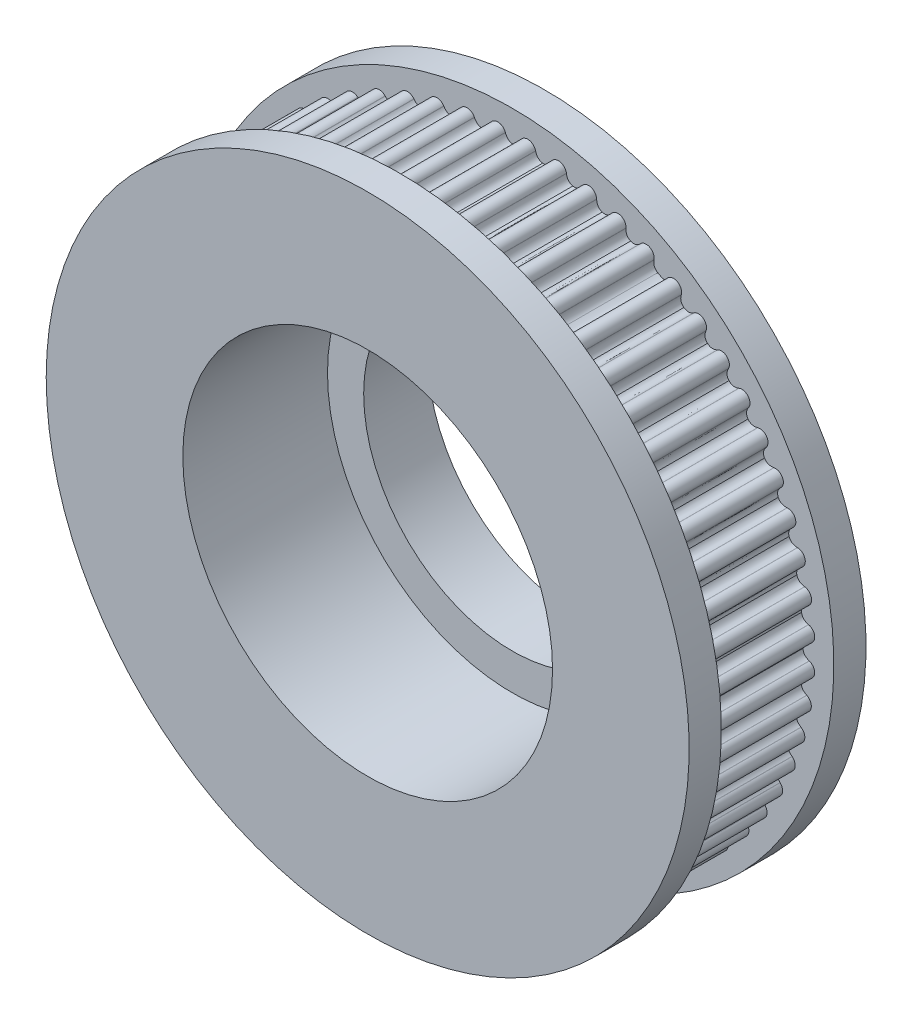
SolidWorks part; units mm, degrees
other "Camera1"
other "Camera2"
other "Camera3"
ref_plane "Front" through (0, 0, 0) normal (0, 0, 1) x (1, 0, 0)
ref_plane "Top" through (0, 0, 0) normal (0, 1, 0) x (1, 0, 0)
ref_plane "Right" through (0, 0, 0) normal (1, 0, 0) x (0, 0, -1)
sketch "Sketch1" plane through (0, 0, 0) normal (1, 0, 0) x (0, 0, -1)
  line L0 (0, 0) -> (-24.4032, 0) construction
  line L2 (0, 11.25) -> (-2, 11.25)
  line L3 (-2, 11.5) -> (-2, 18.85)
  line L4 (-4, 18.85) -> (-11, 18.85)
  line L5 (-13, 18.85) -> (-13, 11.5)
  line L6 (-13, 11.5) -> (-4, 11.5)
  line L7 (-2, 18.85) -> (-2, 20)
  line L9 (-4, 20) -> (-4, 18.85)
  line L10 (-13, 13.3586) -> (-2, 13.3586) construction
  line L11 (-7.5, 18.85) -> (-7.5, 22.0506) construction
  line L12 (-11, 20) -> (-11, 18.85)
  line L14 (-13, 18.85) -> (-13, 20)
  line L15 (-13, 18.85) -> (-11, 18.85) construction
  line L16 (-4, 18.85) -> (-2, 18.85) construction
  line L17 (-13, 20) -> (-11, 20)
  line L18 (-4, 20) -> (-2, 20)
  line L22 (-4, 11.5) -> (-4, 9.25)
  line L23 (-4, 9.25) -> (0, 9.25)
  line L24 (0, 9.25) -> (0, 11.25)
  line L25 (-2, 11.5) -> (-2, 11.25)
  point P24 (-7.5, 13.3586)
  dimension "D2" = 11
  dimension "D3" = 7
  dimension "D4" = 37.7
  dimension "D5" = 40
  dimension "D6" = 2
  dimension "D7" = 22.5
  dimension "D8" = 23
  dimension "D10" = 2
revolve "Revolve1" add sketch "Sketch1" angle 360 about L0
ref_plane "Plane2" through (0, 0, 4) normal (0, 0, 1) x (1, 0, 0)
ref_plane "Plane3" through (0, 0, 11) normal (0, 0, -1) x (-1, 0, 0)
sketch "Sketch3" plane through (0, 0, 4) normal (0, 0, 1) x (1, 0, 0)
  line L0 (0.4895, 18.4804) -> (0.4858, 18.4697)
  line L1 (-0.4323, 18.471) -> (-0.436, 18.4817)
  line L2 (-1.3914, 18.4344) -> (-1.394, 18.4234)
  line L3 (-2.3607, 18.3247) -> (-2.3654, 18.3349)
  line L4 (-3.3107, 18.188) -> (-3.3122, 18.1768)
  line L5 (-4.2632, 17.9775) -> (-4.269, 17.9872)
  line L6 (-5.1937, 17.7423) -> (-5.194, 17.731)
  line L7 (-6.119, 17.4334) -> (-6.1258, 17.4424)
  line L8 (-7.0199, 17.1022) -> (-7.019, 17.0909)
  line L9 (-7.9078, 16.6983) -> (-7.9155, 16.7066)
  line L10 (-8.7691, 16.2747) -> (-8.767, 16.2636)
  line L11 (-9.6099, 15.7803) -> (-9.6184, 15.7877)
  line L12 (-10.4222, 15.269) -> (-10.419, 15.2581)
  line L13 (-11.2067, 14.6893) -> (-11.216, 14.6958)
  line L14 (-11.9612, 14.0959) -> (-11.9568, 14.0855)
  line L15 (-12.6808, 13.4374) -> (-12.6907, 13.4429)
  line L16 (-13.3691, 12.7684) -> (-13.3637, 12.7585)
  line L17 (-14.0159, 12.0383) -> (-14.0263, 12.0427)
  line L18 (-14.6305, 11.301) -> (-14.6241, 11.2917)
  line L19 (-15.1975, 10.5073) -> (-15.2083, 10.5106)
  line L20 (-15.7316, 9.7098) -> (-15.7243, 9.7012)
  line L21 (-16.2125, 8.8612) -> (-16.2236, 8.8633)
  line L22 (-16.6604, 8.0122) -> (-16.6522, 8.0044)
  line L23 (-17.05, 7.118) -> (-17.0612, 7.1189)
  line L24 (-17.4066, 6.2268) -> (-17.3977, 6.22)
  line L25 (-17.7006, 5.2968) -> (-17.7119, 5.2965)
  line L26 (-17.9621, 4.3732) -> (-17.9525, 4.3673)
  line L27 (-18.1573, 3.4175) -> (-18.1685, 3.4161)
  line L28 (-18.3209, 2.4717) -> (-18.3107, 2.4669)
  line L29 (-18.415, 1.5008) -> (-18.426, 1.4983)
  line L30 (-18.4789, 0.5431) -> (-18.4682, 0.5394)
  line L31 (-18.471, -0.4323) -> (-18.4817, -0.436)
  line L32 (-18.4344, -1.3914) -> (-18.4234, -1.394)
  line L33 (-18.3247, -2.3607) -> (-18.3349, -2.3654)
  line L34 (-18.188, -3.3107) -> (-18.1768, -3.3122)
  line L35 (-17.9775, -4.2632) -> (-17.9872, -4.269)
  line L36 (-17.7423, -5.1937) -> (-17.731, -5.194)
  line L37 (-17.4334, -6.119) -> (-17.4424, -6.1258)
  line L38 (-17.1022, -7.0199) -> (-17.0909, -7.019)
  line L39 (-16.6983, -7.9078) -> (-16.7066, -7.9155)
  line L40 (-16.2747, -8.7691) -> (-16.2636, -8.767)
  line L41 (-15.7803, -9.6099) -> (-15.7877, -9.6184)
  line L42 (-15.269, -10.4222) -> (-15.2581, -10.419)
  line L43 (-14.6893, -11.2067) -> (-14.6958, -11.216)
  line L44 (-14.0959, -11.9612) -> (-14.0855, -11.9568)
  line L45 (-13.4374, -12.6808) -> (-13.4429, -12.6907)
  line L46 (-12.7684, -13.3691) -> (-12.7585, -13.3637)
  line L47 (-12.0383, -14.0159) -> (-12.0427, -14.0263)
  line L48 (-11.301, -14.6305) -> (-11.2917, -14.6241)
  line L49 (-10.5073, -15.1975) -> (-10.5106, -15.2083)
  line L50 (-9.7098, -15.7316) -> (-9.7012, -15.7243)
  line L51 (-8.8612, -16.2125) -> (-8.8633, -16.2236)
  line L52 (-8.0122, -16.6604) -> (-8.0044, -16.6522)
  line L53 (-7.118, -17.05) -> (-7.1189, -17.0612)
  line L54 (-6.2268, -17.4066) -> (-6.22, -17.3977)
  line L55 (-5.2968, -17.7006) -> (-5.2965, -17.7119)
  line L56 (-4.3732, -17.9621) -> (-4.3673, -17.9525)
  line L57 (-3.4175, -18.1573) -> (-3.4161, -18.1685)
  line L58 (-2.4717, -18.3209) -> (-2.4669, -18.3107)
  line L59 (-1.5008, -18.415) -> (-1.4983, -18.426)
  line L60 (-0.5431, -18.4789) -> (-0.5394, -18.4682)
  line L61 (0.4323, -18.471) -> (0.436, -18.4817)
  line L62 (1.3914, -18.4344) -> (1.394, -18.4234)
  line L63 (2.3607, -18.3247) -> (2.3654, -18.3349)
  line L64 (3.3107, -18.188) -> (3.3122, -18.1768)
  line L65 (4.2632, -17.9775) -> (4.269, -17.9872)
  line L66 (5.1937, -17.7423) -> (5.194, -17.731)
  line L67 (6.119, -17.4334) -> (6.1258, -17.4424)
  line L68 (7.0199, -17.1022) -> (7.019, -17.0909)
  line L69 (7.9078, -16.6983) -> (7.9155, -16.7066)
  line L70 (8.7691, -16.2747) -> (8.767, -16.2636)
  line L71 (9.6099, -15.7803) -> (9.6184, -15.7877)
  line L72 (10.4222, -15.269) -> (10.419, -15.2581)
  line L73 (11.2067, -14.6893) -> (11.216, -14.6958)
  line L74 (11.9612, -14.0959) -> (11.9568, -14.0855)
  line L75 (12.6808, -13.4374) -> (12.6907, -13.4429)
  line L76 (13.3691, -12.7684) -> (13.3637, -12.7585)
  line L77 (14.0159, -12.0383) -> (14.0263, -12.0427)
  line L78 (14.6305, -11.301) -> (14.6241, -11.2917)
  line L79 (15.1975, -10.5073) -> (15.2083, -10.5106)
  line L80 (15.7316, -9.7098) -> (15.7243, -9.7012)
  line L81 (16.2125, -8.8612) -> (16.2236, -8.8633)
  line L82 (16.6604, -8.0122) -> (16.6522, -8.0044)
  line L83 (17.05, -7.118) -> (17.0612, -7.1189)
  line L84 (17.4066, -6.2268) -> (17.3977, -6.22)
  line L85 (17.7006, -5.2968) -> (17.7119, -5.2965)
  line L86 (17.9621, -4.3732) -> (17.9525, -4.3673)
  line L87 (18.1573, -3.4175) -> (18.1685, -3.4161)
  line L88 (18.3209, -2.4717) -> (18.3107, -2.4669)
  line L89 (18.415, -1.5008) -> (18.426, -1.4983)
  line L90 (18.4789, -0.5431) -> (18.4682, -0.5394)
  line L91 (18.471, 0.4323) -> (18.4817, 0.436)
  line L92 (18.4344, 1.3914) -> (18.4234, 1.394)
  line L93 (18.3247, 2.3607) -> (18.3349, 2.3654)
  line L94 (18.188, 3.3107) -> (18.1768, 3.3122)
  line L95 (17.9775, 4.2632) -> (17.9872, 4.269)
  line L96 (17.7423, 5.1937) -> (17.731, 5.194)
  line L97 (17.4334, 6.119) -> (17.4424, 6.1258)
  line L98 (17.1022, 7.0199) -> (17.0909, 7.019)
  line L99 (16.6983, 7.9078) -> (16.7066, 7.9155)
  line L100 (16.2747, 8.7691) -> (16.2636, 8.767)
  line L101 (15.7803, 9.6099) -> (15.7877, 9.6184)
  line L102 (15.269, 10.4222) -> (15.2581, 10.419)
  line L103 (14.6893, 11.2067) -> (14.6958, 11.216)
  line L104 (14.0959, 11.9612) -> (14.0855, 11.9568)
  line L105 (13.4374, 12.6808) -> (13.4429, 12.6907)
  line L106 (12.7684, 13.3691) -> (12.7585, 13.3637)
  line L107 (12.0383, 14.0159) -> (12.0427, 14.0263)
  line L108 (11.301, 14.6305) -> (11.2917, 14.6241)
  line L109 (10.5073, 15.1975) -> (10.5106, 15.2083)
  line L110 (9.7098, 15.7316) -> (9.7012, 15.7243)
  line L111 (8.8141, 16.2382) -> (8.8162, 16.2492)
  line L112 (7.9639, 16.6835) -> (7.9561, 16.6753)
  line L113 (7.0685, 17.0705) -> (7.0694, 17.0818)
  line L114 (6.1763, 17.4246) -> (6.1695, 17.4156)
  line L115 (5.2454, 17.7159) -> (5.2452, 17.7272)
  line L116 (4.3211, 17.9748) -> (4.3153, 17.9651)
  line L117 (3.3649, 18.1671) -> (3.3634, 18.1783)
  line L118 (2.4186, 18.328) -> (2.4138, 18.3178)
  line L119 (1.4475, 18.4193) -> (1.4449, 18.4303)
  arc A0 (-0.436, 18.4817) -> (-1.3914, 18.4344) centre (-0.9065, 18.3126) ccw
  arc A1 (-2.3654, 18.3349) -> (-3.3107, 18.188) centre (-2.8157, 18.1175) ccw
  arc A2 (-4.269, 17.9872) -> (-5.1937, 17.7423) centre (-4.6941, 17.7239) ccw
  arc A3 (-6.1258, 17.4424) -> (-7.0199, 17.1022) centre (-6.521, 17.1362) ccw
  arc A4 (-7.9155, 16.7066) -> (-8.7691, 16.2747) centre (-8.2765, 16.3607) ccw
  arc A5 (-9.6184, 15.7877) -> (-10.4222, 15.269) centre (-9.9413, 15.4059) ccw
  arc A6 (-11.216, 14.6958) -> (-11.9612, 14.0959) centre (-11.4972, 14.2824) ccw
  arc A7 (-12.6907, 13.4429) -> (-13.3691, 12.7684) centre (-12.9272, 13.0023) ccw
  arc A8 (-14.0263, 12.0427) -> (-14.6305, 11.301) centre (-14.2155, 11.5798) ccw
  arc A9 (-15.2083, 10.5106) -> (-15.7316, 9.7098) centre (-15.348, 10.0305) ccw
  arc A10 (-16.2236, 8.8633) -> (-16.6604, 8.0122) centre (-16.3124, 8.3712) ccw
  arc A11 (-17.0612, 7.1189) -> (-17.4066, 6.2268) centre (-17.0981, 6.6203) ccw
  arc A12 (-17.7119, 5.2965) -> (-17.9621, 4.3732) centre (-17.6964, 4.7968) ccw
  arc A13 (-18.1685, 3.4161) -> (-18.3209, 2.4717) centre (-18.1009, 2.9207) ccw
  arc A14 (-18.426, 1.4983) -> (-18.4789, 0.5431) centre (-18.307, 1.0127) ccw
  arc A15 (-18.4817, -0.436) -> (-18.4344, -1.3914) centre (-18.3126, -0.9065) ccw
  arc A16 (-18.3349, -2.3654) -> (-18.188, -3.3107) centre (-18.1175, -2.8157) ccw
  arc A17 (-17.9872, -4.269) -> (-17.7423, -5.1937) centre (-17.7239, -4.6941) ccw
  arc A18 (-17.4424, -6.1258) -> (-17.1022, -7.0199) centre (-17.1362, -6.521) ccw
  arc A19 (-16.7066, -7.9155) -> (-16.2747, -8.7691) centre (-16.3607, -8.2765) ccw
  arc A20 (-15.7877, -9.6184) -> (-15.269, -10.4222) centre (-15.4059, -9.9413) ccw
  arc A21 (-14.6958, -11.216) -> (-14.0959, -11.9612) centre (-14.2824, -11.4972) ccw
  arc A22 (-13.4429, -12.6907) -> (-12.7684, -13.3691) centre (-13.0023, -12.9272) ccw
  arc A23 (-12.0427, -14.0263) -> (-11.301, -14.6305) centre (-11.5798, -14.2155) ccw
  arc A24 (-10.5106, -15.2083) -> (-9.7098, -15.7316) centre (-10.0305, -15.348) ccw
  arc A25 (-8.8633, -16.2236) -> (-8.0122, -16.6604) centre (-8.3712, -16.3124) ccw
  arc A26 (-7.1189, -17.0612) -> (-6.2268, -17.4066) centre (-6.6203, -17.0981) ccw
  arc A27 (-5.2965, -17.7119) -> (-4.3732, -17.9621) centre (-4.7968, -17.6964) ccw
  arc A28 (-3.4161, -18.1685) -> (-2.4717, -18.3209) centre (-2.9207, -18.1009) ccw
  arc A29 (-1.4983, -18.426) -> (-0.5431, -18.4789) centre (-1.0127, -18.307) ccw
  arc A30 (0.436, -18.4817) -> (1.3914, -18.4344) centre (0.9065, -18.3126) ccw
  arc A31 (2.3654, -18.3349) -> (3.3107, -18.188) centre (2.8157, -18.1175) ccw
  arc A32 (4.269, -17.9872) -> (5.1937, -17.7423) centre (4.6941, -17.7239) ccw
  arc A33 (6.1258, -17.4424) -> (7.0199, -17.1022) centre (6.521, -17.1362) ccw
  arc A34 (7.9155, -16.7066) -> (8.7691, -16.2747) centre (8.2765, -16.3607) ccw
  arc A35 (9.6184, -15.7877) -> (10.4222, -15.269) centre (9.9413, -15.4059) ccw
  arc A36 (11.216, -14.6958) -> (11.9612, -14.0959) centre (11.4972, -14.2824) ccw
  arc A37 (12.6907, -13.4429) -> (13.3691, -12.7684) centre (12.9272, -13.0023) ccw
  arc A38 (14.0263, -12.0427) -> (14.6305, -11.301) centre (14.2155, -11.5798) ccw
  arc A39 (15.2083, -10.5106) -> (15.7316, -9.7098) centre (15.348, -10.0305) ccw
  arc A40 (16.2236, -8.8633) -> (16.6604, -8.0122) centre (16.3124, -8.3712) ccw
  arc A41 (17.0612, -7.1189) -> (17.4066, -6.2268) centre (17.0981, -6.6203) ccw
  arc A42 (17.7119, -5.2965) -> (17.9621, -4.3732) centre (17.6964, -4.7968) ccw
  arc A43 (18.1685, -3.4161) -> (18.3209, -2.4717) centre (18.1009, -2.9207) ccw
  arc A44 (18.426, -1.4983) -> (18.4789, -0.5431) centre (18.307, -1.0127) ccw
  arc A45 (18.4817, 0.436) -> (18.4344, 1.3914) centre (18.3126, 0.9065) ccw
  arc A46 (18.3349, 2.3654) -> (18.188, 3.3107) centre (18.1175, 2.8157) ccw
  arc A47 (17.9872, 4.269) -> (17.7423, 5.1937) centre (17.7239, 4.6941) ccw
  arc A48 (17.4424, 6.1258) -> (17.1022, 7.0199) centre (17.1362, 6.521) ccw
  arc A49 (16.7066, 7.9155) -> (16.2747, 8.7691) centre (16.3607, 8.2765) ccw
  arc A50 (15.7877, 9.6184) -> (15.269, 10.4222) centre (15.4059, 9.9413) ccw
  arc A51 (14.6958, 11.216) -> (14.0959, 11.9612) centre (14.2824, 11.4972) ccw
  arc A52 (13.4429, 12.6907) -> (12.7684, 13.3691) centre (13.0023, 12.9272) ccw
  arc A53 (12.0427, 14.0263) -> (11.301, 14.6305) centre (11.5798, 14.2155) ccw
  arc A54 (10.5106, 15.2083) -> (9.7098, 15.7316) centre (10.0305, 15.348) ccw
  arc A55 (8.8162, 16.2492) -> (7.9639, 16.6835) centre (8.3239, 16.3366) ccw
  arc A56 (7.0694, 17.0818) -> (6.1763, 17.4246) centre (6.5707, 17.1172) ccw
  arc A57 (5.2452, 17.7272) -> (4.3211, 17.9748) centre (4.7454, 17.7103) ccw
  arc A58 (3.3634, 18.1783) -> (2.4186, 18.328) centre (2.8682, 18.1093) ccw
  arc A59 (1.4449, 18.4303) -> (0.4895, 18.4804) centre (0.9596, 18.3099) ccw
  spline S0 degree 3 poles (0.4858, 18.4697) (0.4077, 18.2495) (0.2403, 18.0862) (0.0262, 18.0851) knots 0 0 0 0 1 1 1 1
  spline S1 degree 3 poles (0.0262, 18.0851) (-0.1878, 18.0868) (-0.3548, 18.2506) (-0.4323, 18.471) knots 0 0 0 0 1 1 1 1
  spline S2 degree 3 poles (-1.394, 18.4234) (-1.4515, 18.1875) (-1.5982, 18.0156) (-1.8382, 17.9913) knots 0 0 0 0 1 1 1 1
  spline S3 degree 3 poles (-1.8382, 17.9913) (-2.0782, 17.9665) (-2.2567, 18.1053) (-2.3607, 18.3247) knots 0 0 0 0 1 1 1 1
  spline S4 degree 3 poles (-3.3122, 18.1768) (-3.3447, 17.9362) (-3.4726, 17.7498) (-3.7088, 17.7006) knots 0 0 0 0 1 1 1 1
  spline S5 degree 3 poles (-3.7088, 17.7006) (-3.9448, 17.6509) (-4.1368, 17.7702) (-4.2632, 17.9775) knots 0 0 0 0 1 1 1 1
  spline S6 degree 3 poles (-5.194, 17.731) (-5.2012, 17.4883) (-5.309, 17.2896) (-5.5387, 17.216) knots 0 0 0 0 1 1 1 1
  spline S7 degree 3 poles (-5.5387, 17.216) (-5.7682, 17.1418) (-5.9717, 17.2404) (-6.119, 17.4334) knots 0 0 0 0 1 1 1 1
  spline S8 degree 3 poles (-7.019, 17.0909) (-7.0007, 16.8488) (-7.0871, 16.6399) (-7.3079, 16.5427) knots 0 0 0 0 1 1 1 1
  spline S9 degree 3 poles (-7.3079, 16.5427) (-7.5284, 16.445) (-7.7411, 16.5218) (-7.9078, 16.6983) knots 0 0 0 0 1 1 1 1
  spline S10 degree 3 poles (-8.767, 16.2636) (-8.7236, 16.0248) (-8.7877, 15.808) (-8.9971, 15.6882) knots 0 0 0 0 1 1 1 1
  spline S11 degree 3 poles (-8.9971, 15.6882) (-9.2062, 15.568) (-9.4256, 15.6221) (-9.6099, 15.7803) knots 0 0 0 0 1 1 1 1
  spline S12 degree 3 poles (-10.419, 15.2581) (-10.3508, 15.0251) (-10.3919, 14.8028) (-10.5876, 14.6618) knots 0 0 0 0 1 1 1 1
  spline S13 degree 3 poles (-10.5876, 14.6618) (-10.783, 14.5204) (-11.007, 14.5513) (-11.2067, 14.6893) knots 0 0 0 0 1 1 1 1
  spline S14 degree 3 poles (-11.9568, 14.0855) (-11.8647, 13.8608) (-11.8823, 13.6355) (-12.0622, 13.4748) knots 0 0 0 0 1 1 1 1
  spline S15 degree 3 poles (-12.0622, 13.4748) (-12.2418, 13.3137) (-12.4677, 13.321) (-12.6808, 13.4374) knots 0 0 0 0 1 1 1 1
  spline S16 degree 3 poles (-13.3637, 12.7585) (-13.2485, 12.5447) (-13.2425, 12.3187) (-13.4046, 12.1401) knots 0 0 0 0 1 1 1 1
  spline S17 degree 3 poles (-13.4046, 12.1401) (-13.5664, 11.9611) (-13.7918, 11.9448) (-14.0159, 12.0383) knots 0 0 0 0 1 1 1 1
  spline S18 degree 3 poles (-14.6241, 11.2917) (-14.4872, 11.0912) (-14.4576, 10.867) (-14.6002, 10.6725) knots 0 0 0 0 1 1 1 1
  spline S19 degree 3 poles (-14.6002, 10.6725) (-14.7423, 10.4776) (-14.9648, 10.4378) (-15.1975, 10.5073) knots 0 0 0 0 1 1 1 1
  spline S20 degree 3 poles (-15.7243, 9.7012) (-15.5672, 9.5161) (-15.5143, 9.2963) (-15.6358, 9.0879) knots 0 0 0 0 1 1 1 1
  spline S21 degree 3 poles (-15.6358, 9.0879) (-15.7568, 8.8792) (-15.9739, 8.8163) (-16.2125, 8.8612) knots 0 0 0 0 1 1 1 1
  spline S22 degree 3 poles (-16.6522, 8.0044) (-16.4766, 7.8367) (-16.4011, 7.6237) (-16.5001, 7.4037) knots 0 0 0 0 1 1 1 1
  spline S23 degree 3 poles (-16.5001, 7.4037) (-16.5986, 7.1835) (-16.808, 7.0983) (-17.05, 7.118) knots 0 0 0 0 1 1 1 1
  spline S24 degree 3 poles (-17.3977, 6.22) (-17.2055, 6.0715) (-17.1081, 5.8675) (-17.1836, 5.6384) knots 0 0 0 0 1 1 1 1
  spline S25 degree 3 poles (-17.1836, 5.6384) (-17.2585, 5.4091) (-17.4579, 5.3025) (-17.7006, 5.2968) knots 0 0 0 0 1 1 1 1
  spline S26 degree 3 poles (-17.9525, 4.3673) (-17.7459, 4.2398) (-17.6277, 4.0471) (-17.6788, 3.8114) knots 0 0 0 0 1 1 1 1
  spline S27 degree 3 poles (-17.6788, 3.8114) (-17.7294, 3.5755) (-17.9165, 3.4486) (-18.1573, 3.4175) knots 0 0 0 0 1 1 1 1
  spline S28 degree 3 poles (-18.3107, 2.4669) (-18.0919, 2.3616) (-17.9542, 2.1823) (-17.9804, 1.9425) knots 0 0 0 0 1 1 1 1
  spline S29 degree 3 poles (-17.9804, 1.9425) (-18.006, 1.7027) (-18.1788, 1.5569) (-18.415, 1.5008) knots 0 0 0 0 1 1 1 1
  spline S30 degree 3 poles (-18.4682, 0.5394) (-18.2396, 0.4576) (-18.0839, 0.2937) (-18.0849, 0.0524) knots 0 0 0 0 1 1 1 1
  spline S31 degree 3 poles (-18.0849, 0.0524) (-18.0853, -0.1888) (-18.242, -0.3518) (-18.471, -0.4323) knots 0 0 0 0 1 1 1 1
  spline S32 degree 3 poles (-18.4234, -1.394) (-18.1875, -1.4515) (-18.0156, -1.5982) (-17.9913, -1.8382) knots 0 0 0 0 1 1 1 1
  spline S33 degree 3 poles (-17.9913, -1.8382) (-17.9665, -2.0782) (-18.1053, -2.2567) (-18.3247, -2.3607) knots 0 0 0 0 1 1 1 1
  spline S34 degree 3 poles (-18.1768, -3.3122) (-17.9362, -3.3447) (-17.7498, -3.4726) (-17.7006, -3.7088) knots 0 0 0 0 1 1 1 1
  spline S35 degree 3 poles (-17.7006, -3.7088) (-17.6509, -3.9448) (-17.7702, -4.1368) (-17.9775, -4.2632) knots 0 0 0 0 1 1 1 1
  spline S36 degree 3 poles (-17.731, -5.194) (-17.4883, -5.2012) (-17.2896, -5.309) (-17.216, -5.5387) knots 0 0 0 0 1 1 1 1
  spline S37 degree 3 poles (-17.216, -5.5387) (-17.1418, -5.7682) (-17.2404, -5.9717) (-17.4334, -6.119) knots 0 0 0 0 1 1 1 1
  spline S38 degree 3 poles (-17.0909, -7.019) (-16.8488, -7.0007) (-16.6399, -7.0871) (-16.5427, -7.3079) knots 0 0 0 0 1 1 1 1
  spline S39 degree 3 poles (-16.5427, -7.3079) (-16.445, -7.5284) (-16.5218, -7.7411) (-16.6983, -7.9078) knots 0 0 0 0 1 1 1 1
  spline S40 degree 3 poles (-16.2636, -8.767) (-16.0248, -8.7236) (-15.808, -8.7877) (-15.6882, -8.9971) knots 0 0 0 0 1 1 1 1
  spline S41 degree 3 poles (-15.6882, -8.9971) (-15.568, -9.2062) (-15.6221, -9.4256) (-15.7803, -9.6099) knots 0 0 0 0 1 1 1 1
  spline S42 degree 3 poles (-15.2581, -10.419) (-15.0251, -10.3508) (-14.8028, -10.3919) (-14.6618, -10.5876) knots 0 0 0 0 1 1 1 1
  spline S43 degree 3 poles (-14.6618, -10.5876) (-14.5204, -10.783) (-14.5513, -11.007) (-14.6893, -11.2067) knots 0 0 0 0 1 1 1 1
  spline S44 degree 3 poles (-14.0855, -11.9568) (-13.8608, -11.8647) (-13.6355, -11.8823) (-13.4748, -12.0622) knots 0 0 0 0 1 1 1 1
  spline S45 degree 3 poles (-13.4748, -12.0622) (-13.3137, -12.2418) (-13.321, -12.4677) (-13.4374, -12.6808) knots 0 0 0 0 1 1 1 1
  spline S46 degree 3 poles (-12.7585, -13.3637) (-12.5447, -13.2485) (-12.3187, -13.2425) (-12.1401, -13.4046) knots 0 0 0 0 1 1 1 1
  spline S47 degree 3 poles (-12.1401, -13.4046) (-11.9611, -13.5664) (-11.9448, -13.7918) (-12.0383, -14.0159) knots 0 0 0 0 1 1 1 1
  spline S48 degree 3 poles (-11.2917, -14.6241) (-11.0912, -14.4872) (-10.867, -14.4576) (-10.6725, -14.6002) knots 0 0 0 0 1 1 1 1
  spline S49 degree 3 poles (-10.6725, -14.6002) (-10.4776, -14.7423) (-10.4378, -14.9648) (-10.5073, -15.1975) knots 0 0 0 0 1 1 1 1
  spline S50 degree 3 poles (-9.7012, -15.7243) (-9.5161, -15.5672) (-9.2963, -15.5143) (-9.0879, -15.6358) knots 0 0 0 0 1 1 1 1
  spline S51 degree 3 poles (-9.0879, -15.6358) (-8.8792, -15.7568) (-8.8163, -15.9739) (-8.8612, -16.2125) knots 0 0 0 0 1 1 1 1
  spline S52 degree 3 poles (-8.0044, -16.6522) (-7.8367, -16.4766) (-7.6237, -16.4011) (-7.4037, -16.5001) knots 0 0 0 0 1 1 1 1
  spline S53 degree 3 poles (-7.4037, -16.5001) (-7.1835, -16.5986) (-7.0983, -16.808) (-7.118, -17.05) knots 0 0 0 0 1 1 1 1
  spline S54 degree 3 poles (-6.22, -17.3977) (-6.0715, -17.2055) (-5.8675, -17.1081) (-5.6384, -17.1836) knots 0 0 0 0 1 1 1 1
  spline S55 degree 3 poles (-5.6384, -17.1836) (-5.4091, -17.2585) (-5.3025, -17.4579) (-5.2968, -17.7006) knots 0 0 0 0 1 1 1 1
  spline S56 degree 3 poles (-4.3673, -17.9525) (-4.2398, -17.7459) (-4.0471, -17.6277) (-3.8114, -17.6788) knots 0 0 0 0 1 1 1 1
  spline S57 degree 3 poles (-3.8114, -17.6788) (-3.5755, -17.7294) (-3.4486, -17.9165) (-3.4175, -18.1573) knots 0 0 0 0 1 1 1 1
  spline S58 degree 3 poles (-2.4669, -18.3107) (-2.3616, -18.0919) (-2.1823, -17.9542) (-1.9425, -17.9804) knots 0 0 0 0 1 1 1 1
  spline S59 degree 3 poles (-1.9425, -17.9804) (-1.7027, -18.006) (-1.5569, -18.1788) (-1.5008, -18.415) knots 0 0 0 0 1 1 1 1
  spline S60 degree 3 poles (-0.5394, -18.4682) (-0.4576, -18.2396) (-0.2937, -18.0839) (-0.0524, -18.0849) knots 0 0 0 0 1 1 1 1
  spline S61 degree 3 poles (-0.0524, -18.0849) (0.1888, -18.0853) (0.3518, -18.242) (0.4323, -18.471) knots 0 0 0 0 1 1 1 1
  spline S62 degree 3 poles (1.394, -18.4234) (1.4515, -18.1875) (1.5982, -18.0156) (1.8382, -17.9913) knots 0 0 0 0 1 1 1 1
  spline S63 degree 3 poles (1.8382, -17.9913) (2.0782, -17.9665) (2.2567, -18.1053) (2.3607, -18.3247) knots 0 0 0 0 1 1 1 1
  spline S64 degree 3 poles (3.3122, -18.1768) (3.3447, -17.9362) (3.4726, -17.7498) (3.7088, -17.7006) knots 0 0 0 0 1 1 1 1
  spline S65 degree 3 poles (3.7088, -17.7006) (3.9448, -17.6509) (4.1368, -17.7702) (4.2632, -17.9775) knots 0 0 0 0 1 1 1 1
  spline S66 degree 3 poles (5.194, -17.731) (5.2012, -17.4883) (5.309, -17.2896) (5.5387, -17.216) knots 0 0 0 0 1 1 1 1
  spline S67 degree 3 poles (5.5387, -17.216) (5.7682, -17.1418) (5.9717, -17.2404) (6.119, -17.4334) knots 0 0 0 0 1 1 1 1
  spline S68 degree 3 poles (7.019, -17.0909) (7.0007, -16.8488) (7.0871, -16.6399) (7.3079, -16.5427) knots 0 0 0 0 1 1 1 1
  spline S69 degree 3 poles (7.3079, -16.5427) (7.5284, -16.445) (7.7411, -16.5218) (7.9078, -16.6983) knots 0 0 0 0 1 1 1 1
  spline S70 degree 3 poles (8.767, -16.2636) (8.7236, -16.0248) (8.7877, -15.808) (8.9971, -15.6882) knots 0 0 0 0 1 1 1 1
  spline S71 degree 3 poles (8.9971, -15.6882) (9.2062, -15.568) (9.4256, -15.6221) (9.6099, -15.7803) knots 0 0 0 0 1 1 1 1
  spline S72 degree 3 poles (10.419, -15.2581) (10.3508, -15.0251) (10.3919, -14.8028) (10.5876, -14.6618) knots 0 0 0 0 1 1 1 1
  spline S73 degree 3 poles (10.5876, -14.6618) (10.783, -14.5204) (11.007, -14.5513) (11.2067, -14.6893) knots 0 0 0 0 1 1 1 1
  spline S74 degree 3 poles (11.9568, -14.0855) (11.8647, -13.8608) (11.8823, -13.6355) (12.0622, -13.4748) knots 0 0 0 0 1 1 1 1
  spline S75 degree 3 poles (12.0622, -13.4748) (12.2418, -13.3137) (12.4677, -13.321) (12.6808, -13.4374) knots 0 0 0 0 1 1 1 1
  spline S76 degree 3 poles (13.3637, -12.7585) (13.2485, -12.5447) (13.2425, -12.3187) (13.4046, -12.1401) knots 0 0 0 0 1 1 1 1
  spline S77 degree 3 poles (13.4046, -12.1401) (13.5664, -11.9611) (13.7918, -11.9448) (14.0159, -12.0383) knots 0 0 0 0 1 1 1 1
  spline S78 degree 3 poles (14.6241, -11.2917) (14.4872, -11.0912) (14.4576, -10.867) (14.6002, -10.6725) knots 0 0 0 0 1 1 1 1
  spline S79 degree 3 poles (14.6002, -10.6725) (14.7423, -10.4776) (14.9648, -10.4378) (15.1975, -10.5073) knots 0 0 0 0 1 1 1 1
  spline S80 degree 3 poles (15.7243, -9.7012) (15.5672, -9.5161) (15.5143, -9.2963) (15.6358, -9.0879) knots 0 0 0 0 1 1 1 1
  spline S81 degree 3 poles (15.6358, -9.0879) (15.7568, -8.8792) (15.9739, -8.8163) (16.2125, -8.8612) knots 0 0 0 0 1 1 1 1
  spline S82 degree 3 poles (16.6522, -8.0044) (16.4766, -7.8367) (16.4011, -7.6237) (16.5001, -7.4037) knots 0 0 0 0 1 1 1 1
  spline S83 degree 3 poles (16.5001, -7.4037) (16.5986, -7.1835) (16.808, -7.0983) (17.05, -7.118) knots 0 0 0 0 1 1 1 1
  spline S84 degree 3 poles (17.3977, -6.22) (17.2055, -6.0715) (17.1081, -5.8675) (17.1836, -5.6384) knots 0 0 0 0 1 1 1 1
  spline S85 degree 3 poles (17.1836, -5.6384) (17.2585, -5.4091) (17.4579, -5.3025) (17.7006, -5.2968) knots 0 0 0 0 1 1 1 1
  spline S86 degree 3 poles (17.9525, -4.3673) (17.7459, -4.2398) (17.6277, -4.0471) (17.6788, -3.8114) knots 0 0 0 0 1 1 1 1
  spline S87 degree 3 poles (17.6788, -3.8114) (17.7294, -3.5755) (17.9165, -3.4486) (18.1573, -3.4175) knots 0 0 0 0 1 1 1 1
  spline S88 degree 3 poles (18.3107, -2.4669) (18.0919, -2.3616) (17.9542, -2.1823) (17.9804, -1.9425) knots 0 0 0 0 1 1 1 1
  spline S89 degree 3 poles (17.9804, -1.9425) (18.006, -1.7027) (18.1788, -1.5569) (18.415, -1.5008) knots 0 0 0 0 1 1 1 1
  spline S90 degree 3 poles (18.4682, -0.5394) (18.2396, -0.4576) (18.0839, -0.2937) (18.0849, -0.0524) knots 0 0 0 0 1 1 1 1
  spline S91 degree 3 poles (18.0849, -0.0524) (18.0853, 0.1888) (18.242, 0.3518) (18.471, 0.4323) knots 0 0 0 0 1 1 1 1
  spline S92 degree 3 poles (18.4234, 1.394) (18.1875, 1.4515) (18.0156, 1.5982) (17.9913, 1.8382) knots 0 0 0 0 1 1 1 1
  spline S93 degree 3 poles (17.9913, 1.8382) (17.9665, 2.0782) (18.1053, 2.2567) (18.3247, 2.3607) knots 0 0 0 0 1 1 1 1
  spline S94 degree 3 poles (18.1768, 3.3122) (17.9362, 3.3447) (17.7498, 3.4726) (17.7006, 3.7088) knots 0 0 0 0 1 1 1 1
  spline S95 degree 3 poles (17.7006, 3.7088) (17.6509, 3.9448) (17.7702, 4.1368) (17.9775, 4.2632) knots 0 0 0 0 1 1 1 1
  spline S96 degree 3 poles (17.731, 5.194) (17.4883, 5.2012) (17.2896, 5.309) (17.216, 5.5387) knots 0 0 0 0 1 1 1 1
  spline S97 degree 3 poles (17.216, 5.5387) (17.1418, 5.7682) (17.2404, 5.9717) (17.4334, 6.119) knots 0 0 0 0 1 1 1 1
  spline S98 degree 3 poles (17.0909, 7.019) (16.8488, 7.0007) (16.6399, 7.0871) (16.5427, 7.3079) knots 0 0 0 0 1 1 1 1
  spline S99 degree 3 poles (16.5427, 7.3079) (16.445, 7.5284) (16.5218, 7.7411) (16.6983, 7.9078) knots 0 0 0 0 1 1 1 1
  spline S100 degree 3 poles (16.2636, 8.767) (16.0248, 8.7236) (15.808, 8.7877) (15.6882, 8.9971) knots 0 0 0 0 1 1 1 1
  spline S101 degree 3 poles (15.6882, 8.9971) (15.568, 9.2062) (15.6221, 9.4256) (15.7803, 9.6099) knots 0 0 0 0 1 1 1 1
  spline S102 degree 3 poles (15.2581, 10.419) (15.0251, 10.3508) (14.8028, 10.3919) (14.6618, 10.5876) knots 0 0 0 0 1 1 1 1
  spline S103 degree 3 poles (14.6618, 10.5876) (14.5204, 10.783) (14.5513, 11.007) (14.6893, 11.2067) knots 0 0 0 0 1 1 1 1
  spline S104 degree 3 poles (14.0855, 11.9568) (13.8608, 11.8647) (13.6355, 11.8823) (13.4748, 12.0622) knots 0 0 0 0 1 1 1 1
  spline S105 degree 3 poles (13.4748, 12.0622) (13.3137, 12.2418) (13.321, 12.4677) (13.4374, 12.6808) knots 0 0 0 0 1 1 1 1
  spline S106 degree 3 poles (12.7585, 13.3637) (12.5447, 13.2485) (12.3187, 13.2425) (12.1401, 13.4046) knots 0 0 0 0 1 1 1 1
  spline S107 degree 3 poles (12.1401, 13.4046) (11.9611, 13.5664) (11.9448, 13.7918) (12.0383, 14.0159) knots 0 0 0 0 1 1 1 1
  spline S108 degree 3 poles (11.2917, 14.6241) (11.0912, 14.4872) (10.867, 14.4576) (10.6725, 14.6002) knots 0 0 0 0 1 1 1 1
  spline S109 degree 3 poles (10.6725, 14.6002) (10.4776, 14.7423) (10.4378, 14.9648) (10.5073, 15.1975) knots 0 0 0 0 1 1 1 1
  spline S110 degree 3 poles (9.7012, 15.7243) (9.5161, 15.5672) (9.5993, 15.3388) (9.0425, 15.6621) knots 0 0 0 0 1 1 1 1
  spline S111 degree 3 poles (9.0425, 15.6621) (8.8334, 15.7824) (8.77, 15.9994) (8.8141, 16.2382) knots 0 0 0 0 1 1 1 1
  spline S112 degree 3 poles (7.9561, 16.6753) (7.7889, 16.4993) (7.5761, 16.4231) (7.3558, 16.5215) knots 0 0 0 0 1 1 1 1
  spline S113 degree 3 poles (7.3558, 16.5215) (7.1353, 16.6193) (7.0495, 16.8285) (7.0685, 17.0705) knots 0 0 0 0 1 1 1 1
  spline S114 degree 3 poles (6.1695, 17.4156) (6.0216, 17.2231) (5.8179, 17.125) (5.5886, 17.1999) knots 0 0 0 0 1 1 1 1
  spline S115 degree 3 poles (5.5886, 17.1999) (5.3591, 17.2741) (5.2519, 17.4732) (5.2454, 17.7159) knots 0 0 0 0 1 1 1 1
  spline S116 degree 3 poles (4.3153, 17.9651) (4.1883, 17.7581) (3.996, 17.6394) (3.7601, 17.6898) knots 0 0 0 0 1 1 1 1
  spline S117 degree 3 poles (3.7601, 17.6898) (3.5241, 17.7397) (3.3967, 17.9264) (3.3649, 18.1671) knots 0 0 0 0 1 1 1 1
  spline S118 degree 3 poles (2.4138, 18.3178) (2.3091, 18.0986) (2.1303, 17.9604) (1.8904, 17.9859) knots 0 0 0 0 1 1 1 1
  spline S119 degree 3 poles (1.8904, 17.9859) (1.6505, 18.0109) (1.5042, 18.1832) (1.4475, 18.4193) knots 0 0 0 0 1 1 1 1
extrude "Cut-Extrude1" cut sketch "Sketch3" along normal up to surface (7 mm away) flip side to cut up to plane "Plane3"
sketch "Sketch4" plane through (0, 0, 0) normal (1, 0, 0) x (0, 0, -1)
  line L0 (-4, 21.4747) -> (-4, -21.2713)
  line L1 (-4, 20) -> (-4, -20) construction
split "Split1" trim tools "Sketch4" bodies to split 103 resulting bodies 107 108
